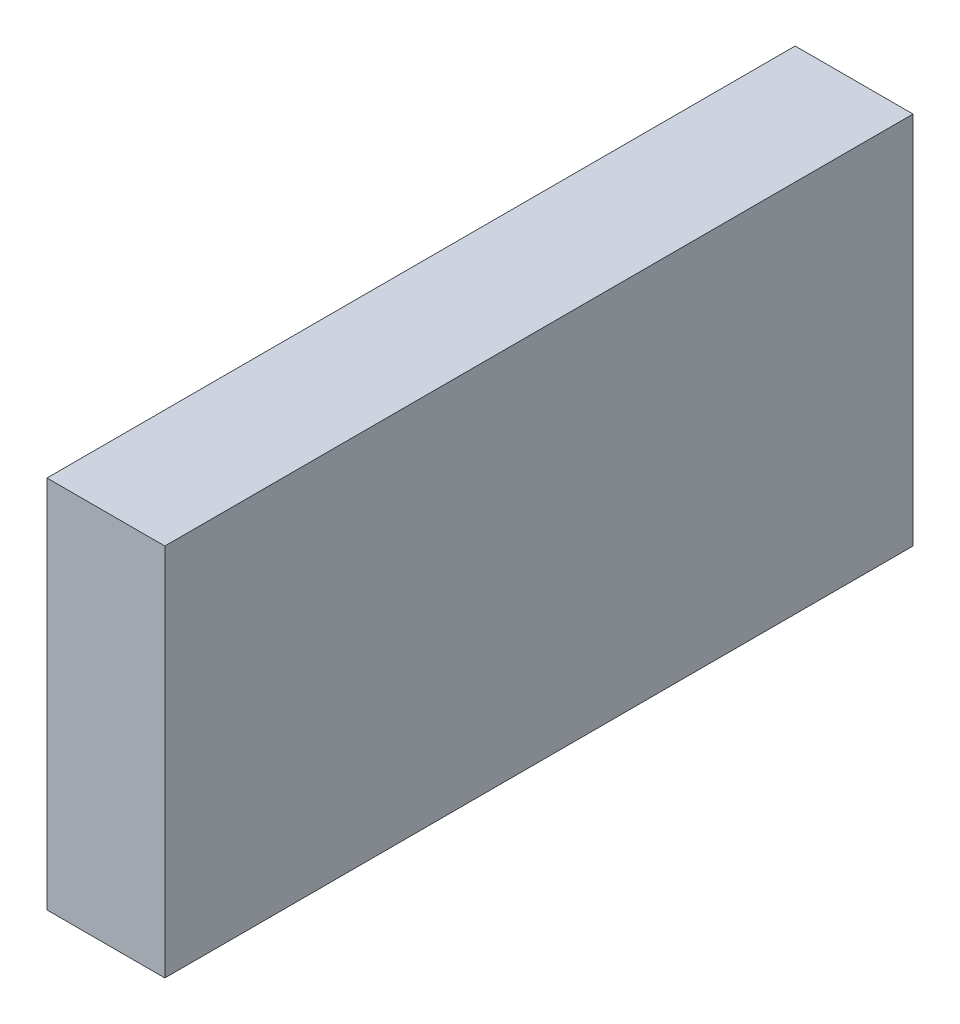
SolidWorks part; units mm, degrees
ref_plane "Front Plane" through (0, 0, 0) normal (0, 0, 1) x (1, 0, 0)
ref_plane "Top Plane" through (0, 0, 0) normal (0, 1, 0) x (1, 0, 0)
ref_plane "Right Plane" through (0, 0, 0) normal (1, 0, 0) x (0, 0, -1)
sketch "Sketch1" plane through (0, 0, 0) normal (1, 0, 0) x (0, 0, -1)
  line L1 (0, 0) -> (40, 0)
  line L2 (0, 0) -> (0, 20)
  line L3 (0, 20) -> (40, 20)
  line L4 (40, 0) -> (40, 20)
extrude "Boss-Extrude1" add sketch "Sketch1" against normal blind 6.3
